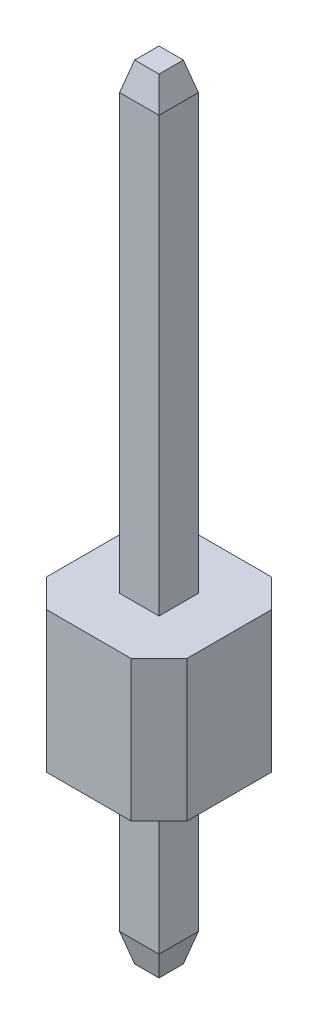
SolidWorks part; units mm, degrees
ref_plane "Front Plane" through (0, 0, 0) normal (0, 0, 1) x (1, 0, 0)
ref_plane "Top Plane" through (0, 0, 0) normal (0, 1, 0) x (1, 0, 0)
ref_plane "Right Plane" through (0, 0, 0) normal (1, 0, 0) x (0, 0, -1)
sketch "Sketch3" plane through (0, 0, 0) normal (0, 1, 0) x (1, 0, 0)
  line L1 (-1.25, 1.25) -> (1.25, 1.25)
  line L2 (-1.25, 1.25) -> (-1.25, -1.25)
  line L3 (-1.25, -1.25) -> (1.25, -1.25)
  line L4 (1.25, 1.25) -> (1.25, -1.25)
  line L5 (-1.25, 1.25) -> (1.25, -1.25) construction
  line L6 (-1.25, -1.25) -> (1.25, 1.25) construction
  point P0 (0, 0)
  point P5 (0, 0)
  dimension "D1" = 2.5
extrude "Boss-Extrude1" add sketch "Sketch3" along normal mid plane 2.5
chamfer "Chamfer1" distance 0.5 angle 45 4 edges at (-1.25, 0, 1.25) (-1.25, 0, -1.25) (1.25, 0, -1.25) (1.25, 0, 1.25)
sketch "Sketch5" plane through (0, 1.25, 0) normal (0, 1, 0) x (1, 0, 0)
  line L1 (0.35, -0.35) -> (-0.35, -0.35)
  line L2 (0.35, -0.35) -> (0.35, 0.35)
  line L3 (0.35, 0.35) -> (-0.35, 0.35)
  line L4 (-0.35, -0.35) -> (-0.35, 0.35)
  line L5 (0.35, -0.35) -> (-0.35, 0.35) construction
  line L6 (0.35, 0.35) -> (-0.35, -0.35) construction
  point P0 (0, 0)
  dimension "D1" = 0.7
extrude "Boss-Extrude2" add sketch "Sketch5" along normal blind 7.7 and the other way blind 5.2 separate body
sketch "Sketch6" plane through (0, 8.95, 0) normal (0, 1, 0) x (1, 0, 0)
  line L4 (-0.35, 0.35) -> (-0.35, -0.35)
  line L5 (-0.35, -0.35) -> (0.35, -0.35)
  line L6 (0.35, -0.35) -> (0.35, 0.35)
  line L7 (0.35, 0.35) -> (-0.35, 0.35)
  line L8 (-0.35, 0.35) -> (-0.35, -0.35)
  line L9 (-0.35, -0.35) -> (0.35, -0.35)
  line L10 (0.35, -0.35) -> (0.35, 0.35)
  line L11 (0.35, 0.35) -> (-0.35, 0.35)
  dimension "D1" = 0
extrude "Boss-Extrude3" add sketch "Sketch6" along normal blind 0.5 draft 15
sketch "Sketch7" plane through (0, -3.95, 0) normal (0, -1, 0) x (1, 0, 0)
  line L4 (-0.35, 0.35) -> (-0.35, -0.35)
  line L5 (-0.35, -0.35) -> (0.35, -0.35)
  line L6 (0.35, -0.35) -> (0.35, 0.35)
  line L7 (0.35, 0.35) -> (-0.35, 0.35)
  line L8 (-0.35, 0.35) -> (-0.35, -0.35)
  line L9 (-0.35, -0.35) -> (0.35, -0.35)
  line L10 (0.35, -0.35) -> (0.35, 0.35)
  line L11 (0.35, 0.35) -> (-0.35, 0.35)
  dimension "D1" = 0
extrude "Boss-Extrude4" add sketch "Sketch7" along normal blind 0.5 draft 15
